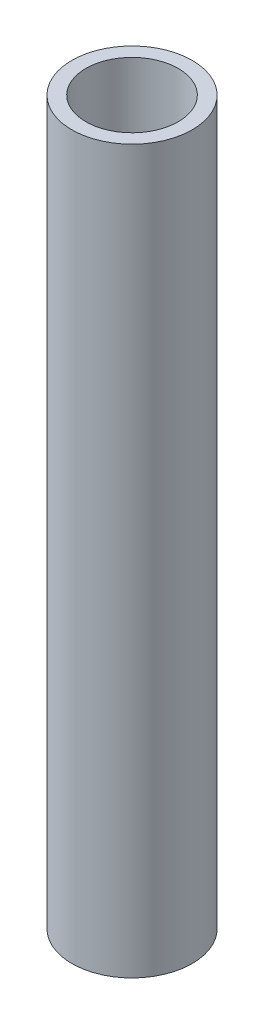
SolidWorks part; units mm, degrees
ref_plane "Front Plane" through (0, 0, 0) normal (0, 0, 1) x (1, 0, 0)
ref_plane "Top Plane" through (0, 0, 0) normal (0, 1, 0) x (1, 0, 0)
ref_plane "Right Plane" through (0, 0, 0) normal (1, 0, 0) x (0, 0, -1)
sketch "Sketch1" plane through (0, 0, 0) normal (0, 1, 0) x (1, 0, 0)
  circle A0 centre (0, 0) radius 6.35
  circle A1 centre (0, 0) radius 4.8768
  dimension "D1" = 12.7
  dimension "D2" = 1.4732
extrude "Boss-Extrude1" add sketch "Sketch1" along normal blind 76.2
